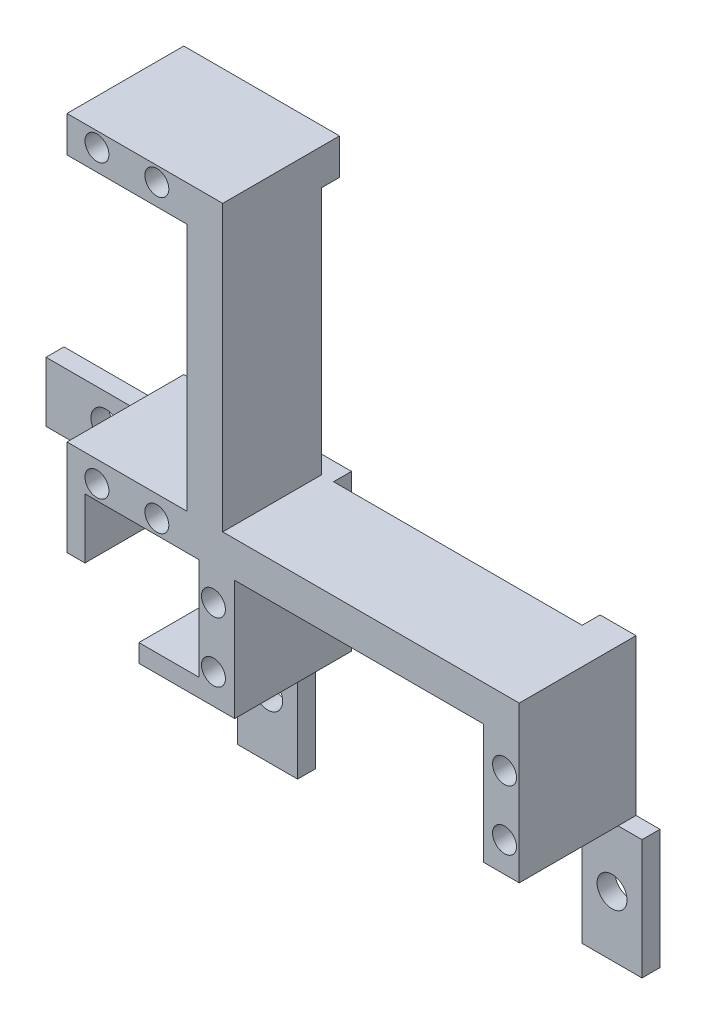
SolidWorks part; units mm, degrees
ref_plane "前视基准面" through (0, 0, 0) normal (0, 0, 1) x (1, 0, 0)
ref_plane "上视基准面" through (0, 0, 0) normal (0, 1, 0) x (1, 0, 0)
ref_plane "右视基准面" through (0, 0, 0) normal (1, 0, 0) x (0, 0, -1)
sketch "草图1" plane through (0, 0, 0) normal (0, 0, 1) x (1, 0, 0)
  line L0 (0, 38.2514) -> (0, 0) construction
  line L1 (0, 0) -> (26.75, 0)
  line L2 (26.75, 0) -> (26.75, -20)
  line L3 (26.75, -20) -> (36.75, -20)
  line L4 (0, -6) -> (20.75, -6)
  line L5 (20.75, -6) -> (20.75, -26)
  line L6 (20.75, -26) -> (36.75, -26)
  line L7 (-36.75, -20) -> (-36.75, -26)
  line L8 (36.75, -20) -> (36.75, -26)
  line L9 (-20.75, -26) -> (-36.75, -26)
  line L10 (-20.75, -6) -> (-20.75, -26)
  line L11 (0, -6) -> (-20.75, -6)
  line L12 (-26.75, -20) -> (-36.75, -20)
  line L13 (-26.75, 0) -> (-26.75, -20)
  line L14 (0, 0) -> (-26.75, 0)
  dimension "D2" = 41.5
  dimension "D3" = 20
  dimension "D4" = 10
  dimension "D5" = 0
  dimension "D1" = 6
extrude "凸台-拉伸1" add sketch "草图1" along normal blind 16.5
sketch "草图3" plane through (0, -20, 0) normal (0, 1, 0) x (1, 0, 0)
  line L1 (36.75, 0) -> (26.75, 0)
  line L2 (36.75, 0) -> (36.75, -16.5)
  line L3 (36.75, -16.5) -> (26.75, -16.5)
  line L4 (26.75, 0) -> (26.75, -16.5)
extrude "切除-拉伸2" cut sketch "草图3" against normal blind 3
sketch "草图4" plane through (0, 0, 16.5) normal (0, 0, 1) x (1, 0, 0)
  line L2 (-26.75, 0) -> (-38.6463, 0)
  line L3 (-26.75, 0) -> (-26.75, -29.0846)
  line L4 (-26.75, -29.0846) -> (-38.6463, -29.0846)
  line L5 (-38.6463, 0) -> (-38.6463, -29.0846)
extrude "切除-拉伸3" cut sketch "草图4" against normal through all
sketch "草图5" plane through (0, 0, 0) normal (0, 0, -1) x (-1, 0, 0)
  line L0 (20.75, -16) -> (-20.75, -16) construction
  line L1 (20.75, -26) -> (20.75, -6) construction
  line L2 (-20.75, -6) -> (-20.75, -26) construction
  line L3 (0, 0) -> (0, -37.9358) construction
  line L4 (-26.75, 0) -> (26.75, 0) construction
  circle A0 centre (-24.3, -11) radius 2
  circle A1 centre (-24.3, -21) radius 2
  circle A2 centre (24.3, -21) radius 2
  circle A3 centre (24.3, -11) radius 2
  dimension "D1" = 4
  dimension "D2" = 4
  dimension "D3" = 10
  dimension "D4" = 5
  dimension "D5" = 24.3
  dimension "D6" = 24.3
extrude "切除-拉伸4" cut sketch "草图5" against normal through all
sketch "草图6" plane through (0, 0, 0) normal (0, 0, -1) x (-1, 0, 0)
  line L1 (-26.75, -23) -> (-36.75, -23)
  line L2 (-26.75, -23) -> (-26.75, -46)
  line L3 (-26.75, -46) -> (-36.75, -46)
  line L4 (-36.75, -23) -> (-36.75, -46)
  dimension "D1" = 23
extrude "凸台-拉伸2" add sketch "草图6" along normal blind 3
sketch "草图7" plane through (0, 0, -3) normal (0, 0, -1) x (-1, 0, 0)
  line L0 (-36.75, -46) -> (-26.75, -46) construction
  line L1 (-36.75, -23) -> (-36.75, -46) construction
  circle A0 centre (-31.75, -36) radius 2.5
  dimension "D1" = 5
  dimension "D2" = 10
  dimension "D3" = 5
extrude "切除-拉伸5" cut sketch "草图7" against normal blind 3
sketch "草图8" plane through (0, 0, 0) normal (0, 0, -1) x (-1, 0, 0)
  line L0 (-36.75, -46) -> (-26.75, -46) construction
  line L1 (26.75, 0) -> (20.75, 0)
  line L2 (26.75, 0) -> (26.75, -26)
  line L3 (26.75, -46) -> (20.75, -46)
  line L4 (20.75, 0) -> (20.75, -46)
  line L6 (26.75, -46) -> (30.75, -46)
  line L8 (26.75, -26) -> (30.75, -26)
  line L9 (30.75, -46) -> (30.75, -26)
  line L11 (-20.75, -26) -> (-26.75, -26)
  line L12 (-20.75, -26) -> (-20.75, 0)
  line L13 (-20.75, 0) -> (-26.75, 0)
  line L14 (-26.75, -26) -> (-26.75, 0)
  circle A0 centre (24.3, -21) radius 2 construction
  circle A1 centre (24.3, -21) radius 2
  circle A2 centre (24.3, -11) radius 2 construction
  circle A3 centre (24.3, -11) radius 2
  circle A4 centre (-24.3, -11) radius 2 construction
  circle A5 centre (-24.3, -21) radius 2 construction
  circle A6 centre (-24.3, -11) radius 2
  circle A7 centre (-24.3, -21) radius 2
  dimension "D1" = 6
  dimension "D2" = 20
  dimension "D3" = 10
extrude "凸台-拉伸3" add sketch "草图8" along normal blind 3
sketch "草图9" plane through (0, 0, -3) normal (0, 0, -1) x (-1, 0, 0)
  line L0 (30.75, -46) -> (30.75, -26) construction
  line L1 (20.75, -46) -> (30.75, -46) construction
  circle A0 centre (25.75, -36) radius 2.5
  dimension "D1" = 5
  dimension "D2" = 5
  dimension "D3" = 10
extrude "切除-拉伸6" cut sketch "草图9" against normal blind 3
mirror "镜向1" about plane through (36.75, -20, 16.5) normal (-1, 0, 0) of bodies 114
sketch "草图10" plane through (0, 0, -3) normal (0, 0, -1) x (-1, 0, 0)
  line L0 (-46.75, -46) -> (-26.75, -46) construction
  line L1 (-36.75, -46) -> (37.944, -46)
  line L2 (-36.75, -46) -> (-36.75, 6.0951)
  line L3 (-36.75, 6.0951) -> (37.944, 6.0951)
  line L4 (37.944, -46) -> (37.944, 6.0951)
extrude "切除-拉伸7" cut sketch "草图10" against normal through all
ref_plane "基准面1" through (23.375, -23.375, 0) normal (-0.7071, 0.7071, 0) x (0, 0, -1)
sketch "草图13" plane through (0, 0, -3) normal (0, 0, -1) x (-1, 0, 0)
  line L1 (-24.75, -6) -> (-50.75, -6)
  line L2 (-24.75, -6) -> (-24.75, 0)
  line L3 (-24.75, 47.5) -> (-50.75, 47.5)
  line L4 (-50.75, -6) -> (-50.75, 47.5)
  line L6 (-36.75, -23) -> (-46.75, -23) construction
  line L9 (-46.75, 0) -> (-46.75, -23) construction
  line L11 (-24.75, 41.5) -> (-44.75, 41.5)
  line L12 (-44.75, 20.75) -> (-8.0679, 20.75) construction
  line L13 (-24.75, 0) -> (-44.75, 0)
  line L14 (-44.75, 41.5) -> (-44.75, 0)
  line L16 (-24.75, 41.5) -> (-24.75, 47.5)
  line L17 (-34.75, 41.5) -> (-34.75, 0) construction
  circle A1 centre (-29.75, -3.55) radius 2
  circle A2 centre (-39.75, -3.55) radius 2
  circle A6 centre (-39.75, 45.05) radius 2
  circle A7 centre (-29.75, 45.05) radius 2
  dimension "D8" = 4
  dimension "D9" = 4
  dimension "D10" = 10
  dimension "D11" = 48.6
  dimension "D12" = 5
  dimension "D13" = 5
  dimension "D1" = 26
  dimension "D2" = 17
  dimension "D3" = 53.5
  dimension "D4" = 4
  dimension "D5" = 20
  dimension "D6" = 41.5
  dimension "D7" = 6
extrude "凸台-拉伸4" add sketch "草图13" against normal up to surface (19.5 mm away) up to face at (66.15, -16.2, 16.5)
sketch "草图14" plane through (0, 0, -3) normal (0, 0, -1) x (-1, 0, 0)
  line L0 (-44.75, 0) -> (-44.75, 41.5) construction
  line L1 (-44.75, 41.5) -> (-50.75, 41.5)
  line L2 (-44.75, 41.5) -> (-44.75, 0)
  line L3 (-44.75, 0) -> (-50.75, 0)
  line L4 (-50.75, 41.5) -> (-50.75, 0)
  line L7 (-24.75, 41.5) -> (-24.75, 0) construction
  line L8 (-24.75, 20.75) -> (-33.9969, 20.75) construction
  dimension "D1" = 41.5
  dimension "D2" = 6
  dimension "D3" = 20.75
extrude "切除-拉伸9" cut sketch "草图14" against normal up to surface (3 mm away) up to face at (73.5, -3, 0)
sketch "草图15" plane through (0, 0, -3) normal (0, 0, -1) x (-1, 0, 0)
  line L1 (-4.75, -6) -> (-27.75, -6)
  line L2 (-4.75, -6) -> (-4.75, -16)
  line L3 (-4.75, -16) -> (-27.75, -16)
  line L4 (-27.75, -6) -> (-27.75, -16)
  line L6 (-24.75, -6) -> (-24.75, 0) construction
  line L9 (-46.75, -6) -> (-24.75, -6) construction
  circle A0 centre (-14.75, -11) radius 2.5
  point P6 (0, 0)
  point P7 (0, 0)
  point P10 (0, 0)
  point P11 (-13.2099, -11)
  point P14 (0, 0)
  point P15 (0, 0)
  point P16 (-17.1518, -11)
  point P17 (-14.1385, -11)
  point P18 (0, 0)
  point P19 (0, 0)
  point P20 (0, 0)
  point P21 (0, 0)
  point P22 (0, 0)
  point P23 (0, 0)
  point P24 (0, 0)
  point P25 (0, 0)
  point P26 (0, 0)
  point P27 (-4.75, -11)
  dimension "D5" = 10
  dimension "D6" = 5
  dimension "D7" = 5
  dimension "D1" = 3
  dimension "D2" = 10
  dimension "D3" = 23
  dimension "D4" = 0
extrude "凸台-拉伸5" add sketch "草图15" against normal blind 3
sketch "草图16" plane through (0, 0, 0) normal (0, 0, 1) x (1, 0, 0)
  line L0 (24.75, -6) -> (27.75, -6) construction
  line L1 (27.75, -16) -> (24.75, -16)
  line L2 (27.75, -16) -> (27.75, -6)
  line L3 (27.75, -6) -> (24.75, -6)
  line L4 (24.75, -16) -> (24.75, -6)
  line L5 (4.75, -6) -> (24.75, -6) construction
extrude "凸台-拉伸6" add sketch "草图16" along normal up to surface (16.5 mm away) up to face at (52.8611, 0.2222, 16.5)
